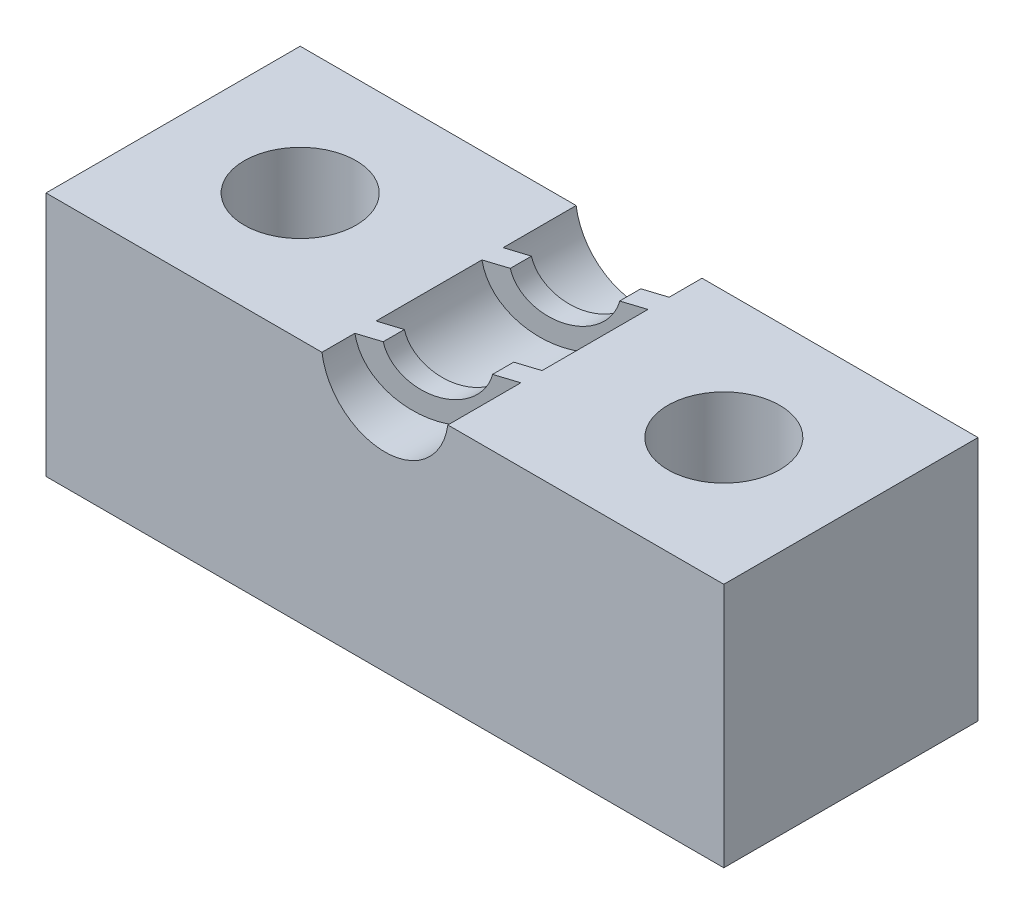
SolidWorks part; units mm, degrees
ref_plane "前视基准面" through (0, 0, 0) normal (0, 0, 1) x (1, 0, 0)
ref_plane "上视基准面" through (0, 0, 0) normal (0, 1, 0) x (1, 0, 0)
ref_plane "右视基准面" through (0, 0, 0) normal (1, 0, 0) x (0, 0, -1)
other "Configuration Table"
sketch "草图1" plane through (0, 0, 0) normal (0, 0, 1) x (1, 0, 0)
  line L1 (-8, -6) -> (8, -6)
  line L2 (-8, -6) -> (-8, 6)
  line L3 (-8, 6) -> (8, 6)
  line L4 (8, -6) -> (8, 6)
  line L5 (-8, -6) -> (8, 6) construction
  line L6 (-8, 6) -> (8, -6) construction
  circle A0 centre (0, 0) radius 1.5
  point P0 (0, 0)
  dimension "D3" = 3
  dimension "D1" = 16
  dimension "D2" = 12
extrude "凸台-拉伸1" add sketch "草图1" along normal mid plane 6
sketch "草图2" plane through (0, 0, 3) normal (0, 0, 1) x (1, 0, 0)
  circle A0 centre (0, 0) radius 1.5 construction
  circle A1 centre (0, 0) radius 1.5
curve "螺旋线/涡状线1" [suppressed] pitch 3 height 6 turns 2
sketch "草图4" [suppressed] plane through (0, 0, 0) normal (0, 1, 0) x (1, 0, 0)
  line L0 (0, 4.8801) -> (0, -4.2719) construction
sketch3d "3D草图1" [suppressed]
  spline S0 degree 3 poles (-942.1956, -331.2134, -36.5595) (37.1464, -47.6823, 7.9547) (5.73, 5.65, 5.1859) (-1.0881, 1.0883, 2.625) (-1.4219, 0.589, 2.4375) (-1.539, 0, 2.25) (-1.4219, -0.589, 2.0625) (-1.0883, -1.0883, 1.875) (-0.589, -1.4219, 1.6875) (0, -1.5391, 1.5) (0.589, -1.4219, 1.3125) (1.0883, -1.0883, 1.125) (1.4219, -0.589, 0.9375) (1.5391, 0, 0.75) (1.4219, 0.589, 0.5625) (1.0883, 1.0883, 0.375) (0.589, 1.4219, 0.1875) (0, 1.5391, 0) (-0.589, 1.4219, -0.1875) (-1.0883, 1.0883, -0.375) (-1.4219, 0.589, -0.5625) (-1.5391, 0, -0.75) (-1.4219, -0.589, -0.9375) (-1.0883, -1.0883, -1.125) (-0.589, -1.4219, -1.3125) (0, -1.5391, -1.5) (0.589, -1.4219, -1.6875) (1.0883, -1.0883, -1.875) (1.4219, -0.589, -2.0625) (1.539, 0, -2.25) (1.4219, 0.589, -2.4375) (1.0881, 1.0883, -2.625) (-5.73, 5.65, -5.1859) (-37.1462, -47.6821, -7.9547) (942.1897, -331.2117, 36.5592) knots -1.18812 -1.18812 -1.18812 -1.18812 0.03125 0.0625 0.09375 0.125 0.15625 0.1875 0.21875 0.25 0.28125 0.3125 0.34375 0.375 0.40625 0.4375 0.46875 0.5 0.53125 0.5625 0.59375 0.625 0.65625 0.6875 0.71875 0.75 0.78125 0.8125 0.84375 0.875 0.90625 0.9375 0.96875 2.188117 2.188117 2.188117 2.188117 only from (0, 1.5, 3) to (0, 1.5, -3) construction
  spline S1 degree 3 poles (0, 1.5, 3) (-0.1952, 1.5, 2.9379) (-0.5895, 1.4219, 2.8123) (-1.0881, 1.0883, 2.625) (-1.4219, 0.589, 2.4375) (-1.539, 0, 2.25) (-1.4219, -0.589, 2.0625) (-1.0883, -1.0883, 1.875) (-0.589, -1.4219, 1.6875) (0, -1.5391, 1.5) (0.589, -1.4219, 1.3125) (1.0883, -1.0883, 1.125) (1.4219, -0.589, 0.9375) (1.5391, 0, 0.75) (1.4219, 0.589, 0.5625) (1.0883, 1.0883, 0.375) (0.589, 1.4219, 0.1875) (0, 1.5391, 0) (-0.589, 1.4219, -0.1875) (-1.0883, 1.0883, -0.375) (-1.4219, 0.589, -0.5625) (-1.5391, 0, -0.75) (-1.4219, -0.589, -0.9375) (-1.0883, -1.0883, -1.125) (-0.589, -1.4219, -1.3125) (0, -1.5391, -1.5) (0.589, -1.4219, -1.6875) (1.0883, -1.0883, -1.875) (1.4219, -0.589, -2.0625) (1.539, 0, -2.25) (1.4219, 0.589, -2.4375) (1.0881, 1.0883, -2.625) (0.5895, 1.4219, -2.8123) (0.1952, 1.5, -2.9379) (0, 1.5, -3) knots 0 0 0 0 0.03125 0.0625 0.09375 0.125 0.15625 0.1875 0.21875 0.25 0.28125 0.3125 0.34375 0.375 0.40625 0.4375 0.46875 0.5 0.53125 0.5625 0.59375 0.625 0.65625 0.6875 0.71875 0.75 0.78125 0.8125 0.84375 0.875 0.90625 0.9375 0.96875 1 1 1 1
sketch3d "3D草图2" [suppressed]
  line L0 (0, 1.5, 3) -> (0, 0, 3) construction
  line L1 (0, 0, -4.8801) -> (0, 0, 4.2719) construction
  line L2 (0, 1.5, 3) -> (0, 0.3536, 3)
surface "曲面-扫描1" [suppressed]
thicken "加厚3" [suppressed] surfaces to thicken 107 thickness 0.225 parameters "D1"=0.225
sketch "草图6" plane through (0, 0, 0) normal (0, 1, 0) x (1, 0, 0)
  line L0 (-1.5, -3) -> (1.5, -3) construction
  line L1 (1.5, 3) -> (-1.5, 3) construction
  line L2 (-1.5, -3) -> (1.5, -3)
  line L3 (1.5, 3) -> (-1.5, 3)
  line L4 (-1.5, 3) -> (-1.5, -3)
  line L5 (1.5, -3) -> (1.5, 3)
  line L6 (-1.5, 0.7724) -> (1.5, 1.7276)
  line L7 (1.5, 1.7276) -> (1.5, 2.2276)
  line L8 (1.5, 2.2276) -> (-1.5, 1.2724)
  line L9 (-1.5, -1.7276) -> (1.5, -0.7724)
  line L10 (-1.5, -2.2276) -> (1.5, -1.2724)
  line L11 (-2.0945, -0.6668) -> (3.135, 0.9981) construction
  line L12 (-3.1004, 0) -> (4.2723, 0) construction
  dimension "D1" = 2.5
  dimension "D2" = 0.5
  dimension "D3" = 0.5
  dimension "D4" = 17.66
extrude "凸台-拉伸2" add sketch "草图6" against normal up to surface (6 mm away) contours L4 L10 L5 L9 | L5 L8 L4 L6 up to face at (0, -6, 0)
sketch "草图7" plane through (0, 0, 0) normal (0, 0, 1) x (1, 0, 0)
  line L0 (0, 0) -> (-0.979, -0.2039)
  line L1 (0, 0) -> (0.979, -0.2039)
  line L2 (-0.979, -0.2039) -> (-8, -0.2039)
  line L3 (0.979, -0.2039) -> (8, -0.2039)
  line L6 (8, -6) -> (8, 6)
  line L7 (-8, -6) -> (8, -6)
  line L8 (-8, 6) -> (-8, -6)
  line L9 (8, 6) -> (-8, 6)
  line L10 (8, -6) -> (8, 6)
  line L11 (-8, -6) -> (8, -6)
  line L12 (-8, 6) -> (-8, -6)
  line L13 (8, 6) -> (-8, 6)
  circle A0 centre (0, 0) radius 1
  dimension "D1" = 2
  dimension "D2" = 0
  dimension "D3" = 156.47
extrude "切除-拉伸2" cut sketch "草图7" against normal through all both and the other way through all contours A0 L3 L10 L13 L12 L2 | L1 A0 L0 | L0 A0 L1
sketch "草图8" plane through (0, 0, 0) normal (0, 1, 0) x (1, 0, 0)
  line L0 (0, 5.5834) -> (0, -5.0797) construction
  circle A0 centre (-5, 0) radius 1.32
  circle A1 centre (5, 0) radius 1.32
  dimension "D1" = 2.64
  dimension "D2" = 2.64
  dimension "D3" = 10
extrude "切除-拉伸3" cut sketch "草图8" against normal through all
equation "\"x\"=0.8094"
